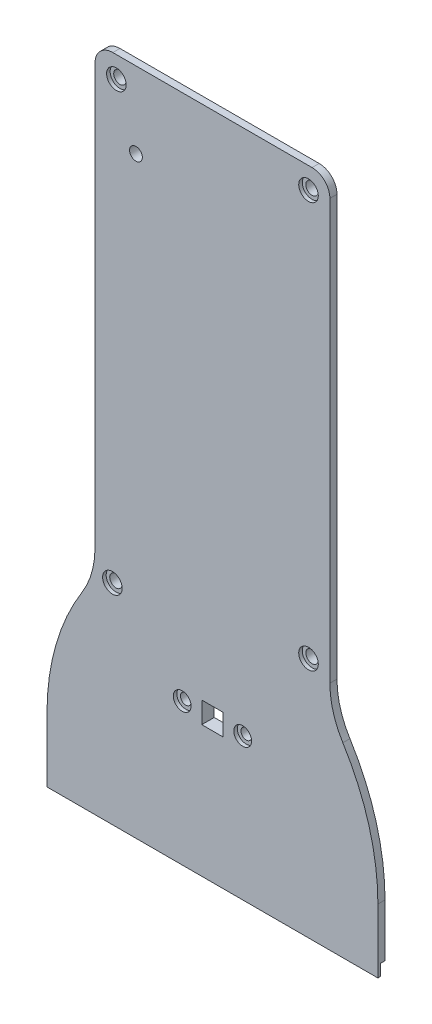
SolidWorks part; units mm, degrees
ref_plane "Front Plane" through (0, 0, 0) normal (0, 0, 1) x (1, 0, 0)
ref_plane "Top Plane" through (0, 0, 0) normal (0, 1, 0) x (1, 0, 0)
ref_plane "Right Plane" through (0, 0, 0) normal (1, 0, 0) x (0, 0, -1)
sketch "Sketch1" plane through (0, 0, 0) normal (0, 0, 1) x (1, 0, 0)
  line L0 (44, 18) -> (44, 3) construction
  line L1 (-30, 185.0054) -> (30, 185.0054) construction
  line L2 (-30, 185.0054) -> (-30, 65.0054) construction
  line L3 (-30, 65.0054) -> (30, 65.0054) construction
  line L4 (30, 185.0054) -> (30, 65.0054) construction
  line L5 (46.5, 3) -> (-46.5, 3) construction
  line L6 (-44, 3) -> (-44, 18) construction
  line L7 (44, 18) -> (44, 3) construction
  line L8 (44, 3) -> (-44, 3) construction
  line L9 (-44, 3) -> (-44, 18) construction
  line L10 (-44, 3) -> (-46.5, 3) construction
  line L11 (46.5, 3) -> (44, 3) construction
  line L12 (-43.5, 3.5) -> (-43.5, 18)
  line L13 (43.5, 3.5) -> (-43.5, 3.5)
  line L14 (43.5, 18) -> (43.5, 3.5)
  line L15 (29.5, 184.5054) -> (29.5, 65.0054)
  line L16 (-29.5, 184.5054) -> (29.5, 184.5054)
  line L17 (-29.5, 184.5054) -> (-29.5, 65.0054)
  line L18 (-29.552, 64.9761) -> (-29.5, 65.0054)
  line L19 (29.5, 65.0054) -> (29.552, 64.9761)
  arc A0 (44, 18) -> (34.5208, 51.0054) centre (-18.2002, 18) ccw construction
  arc A1 (30.0511, 65.0054) -> (34.5208, 51.0054) centre (59.6645, 66.7464) ccw construction
  arc A2 (-34.5208, 51.0054) -> (-44, 18) centre (18.2002, 18) ccw construction
  arc A3 (-34.5208, 51.0054) -> (-30.0511, 65.0054) centre (-59.6645, 66.7464) ccw construction
  arc A4 (44, 18) -> (34.5208, 51.0054) centre (-18.2002, 18) ccw construction
  arc A5 (30.0511, 65.0054) -> (34.5208, 51.0054) centre (59.6645, 66.7464) ccw construction
  arc A6 (-34.5208, 51.0054) -> (-44, 18) centre (18.2002, 18) ccw construction
  arc A7 (-34.5208, 51.0054) -> (-30.0511, 65.0054) centre (-59.6645, 66.7464) ccw construction
  arc A8 (-34.097, 50.7401) -> (-29.552, 64.9761) centre (-59.6645, 66.7464) ccw
  arc A9 (-34.097, 50.7401) -> (-43.5, 18) centre (18.2002, 18) ccw
  arc A10 (43.5, 18) -> (34.097, 50.7401) centre (-18.2002, 18) ccw
  arc A11 (29.552, 64.9761) -> (34.097, 50.7401) centre (59.6645, 66.7464) ccw
  dimension "D1" = 0.5
extrude "Boss-Extrude1" add sketch "Sketch1" against normal blind 1.5
sketch "Sketch2" plane through (0, 0, 0) normal (0, 0, 1) x (1, 0, 0)
  line L0 (-46.5, 3) -> (-46.5, 18) construction
  line L1 (-46.5, 3) -> (-46.5, 0) construction
  line L2 (46.5, 0) -> (-46.5, 0) construction
  line L3 (46.5, 3) -> (46.5, 0) construction
  line L4 (46.5, 3) -> (46.5, 18) construction
  line L5 (33, 65.0054) -> (33, 183.0054) construction
  line L6 (28, 188.0054) -> (-28, 188.0054) construction
  line L7 (-33, 65.0054) -> (-33, 183.0054) construction
  line L8 (-46.5, 3) -> (-46.5, 18)
  line L9 (-46.5, 3) -> (-46.5, 0)
  line L10 (46.5, 0) -> (-46.5, 0)
  line L11 (46.5, 3) -> (46.5, 0)
  line L12 (46.5, 3) -> (46.5, 18)
  line L13 (33, 65.0054) -> (33, 183.0054)
  line L14 (28, 188.0054) -> (-28, 188.0054)
  line L15 (-33, 65.0054) -> (-33, 183.0054)
  arc A0 (-36.6398, 52.332) -> (-33, 65.0054) centre (-56.8836, 65.0054) ccw construction
  arc A1 (-36.6398, 52.332) -> (-46.5, 18) centre (18.2002, 18) ccw construction
  arc A2 (46.5, 18) -> (36.6398, 52.332) centre (-18.2002, 18) ccw construction
  arc A3 (33, 65.0054) -> (36.6398, 52.332) centre (56.8836, 65.0054) ccw construction
  arc A4 (33, 183.0054) -> (28, 188.0054) centre (28, 183.0054) ccw construction
  arc A5 (-28, 188.0054) -> (-33, 183.0054) centre (-28, 183.0054) ccw construction
  arc A6 (-36.6398, 52.332) -> (-33, 65.0054) centre (-56.8836, 65.0054) ccw
  arc A7 (-36.6398, 52.332) -> (-46.5, 18) centre (18.2002, 18) ccw
  arc A8 (46.5, 18) -> (36.6398, 52.332) centre (-18.2002, 18) ccw
  arc A9 (33, 65.0054) -> (36.6398, 52.332) centre (56.8836, 65.0054) ccw
  arc A10 (33, 183.0054) -> (28, 188.0054) centre (28, 183.0054) ccw
  arc A11 (-28, 188.0054) -> (-33, 183.0054) centre (-28, 183.0054) ccw
extrude "Boss-Extrude2" add sketch "Sketch2" along normal blind 2
sketch "Sketch3" plane through (-46.5, 0, 0) normal (-1, 0, 0) x (0, 0, 1)
  line L1 (0, 0) -> (1.2, 0)
  line L2 (0, 0) -> (0, 3.2)
  line L3 (0, 3.2) -> (1.2, 3.2)
  line L4 (1.2, 0) -> (1.2, 3.2)
  dimension "D1" = 1.2
  dimension "D2" = 3.2
extrude "Cut-Extrude1" cut sketch "Sketch3" against normal through all
sketch "Sketch4" plane through (0, 0, 2) normal (0, 0, 1) x (1, 0, 0)
  line L11 (-22.5, 165.1154) -> (-20.5, 168.1154) construction
  line L15 (3, 42.9121) -> (-3, 42.9121)
  line L16 (3, 36.9121) -> (3, 42.9121)
  line L17 (-3, 36.9121) -> (3, 36.9121)
  line L18 (-3, 42.9121) -> (-3, 36.9121)
  line L19 (3, 42.9121) -> (-3, 42.9121)
  line L20 (3, 36.9121) -> (3, 42.9121)
  line L21 (-3, 36.9121) -> (3, 36.9121)
  line L22 (-3, 42.9121) -> (-3, 36.9121)
  circle A0 centre (-27, 182.0054) radius 1.75
  circle A1 centre (27, 182.0054) radius 1.75
  circle A2 centre (-28.1178, 58.8809) radius 1.75
  circle A3 centre (27, 68.0054) radius 1.75
  circle A4 centre (-8.5, 39.9121) radius 1.5
  circle A5 centre (8.5, 39.9121) radius 1.5
  point P18 (-21.5, 166.6154)
  dimension "D1" = 3.5
  dimension "D2" = 3.5
  dimension "D3" = 3.5
  dimension "D4" = 3.5
  dimension "D6" = 3
  dimension "D7" = 3
  dimension "D5" = 0.5
extrude "Cut-Extrude2" cut sketch "Sketch4" against normal through all
sketch "Sketch5" plane through (0, 0, 2) normal (0, 0, 1) x (1, 0, 0)
  circle A0 centre (-27, 182.0054) radius 1.75 construction
  circle A1 centre (27, 182.0054) radius 1.75 construction
  circle A5 centre (-28.1178, 58.8809) radius 1.75 construction
  circle A8 centre (27, 68.0054) radius 1.75 construction
  circle A12 centre (-8.5, 39.9121) radius 1.5 construction
  circle A17 centre (8.5, 39.9121) radius 1.5 construction
  circle A29 centre (27, 182.0054) radius 1.75 construction
  circle A30 centre (-27, 182.0054) radius 1.75 construction
  circle A31 centre (27, 68.0054) radius 1.75 construction
  circle A32 centre (8.5, 39.9121) radius 1.5 construction
  circle A33 centre (-8.5, 39.9121) radius 1.5 construction
  circle A34 centre (-28.1178, 58.8809) radius 1.75 construction
  circle A35 centre (27, 182.0054) radius 2.75
  circle A36 centre (-27, 182.0054) radius 2.75
  circle A37 centre (-28.1178, 58.8809) radius 2.75
  circle A38 centre (-8.5, 39.9121) radius 2.5
  circle A39 centre (8.5, 39.9121) radius 2.5
  circle A40 centre (27, 68.0054) radius 2.75
  dimension "D1" = 1
extrude "Cut-Extrude3" cut sketch "Sketch5" against normal blind 1
sketch "Sketch6" plane through (0, 0, 2) normal (0, 0, 1) x (1, 0, 0)
  circle A0 centre (-21.5, 166.6154) radius 1.8
  dimension "D1" = 3.6
extrude "Cut-Extrude4" cut sketch "Sketch6" against normal through all
